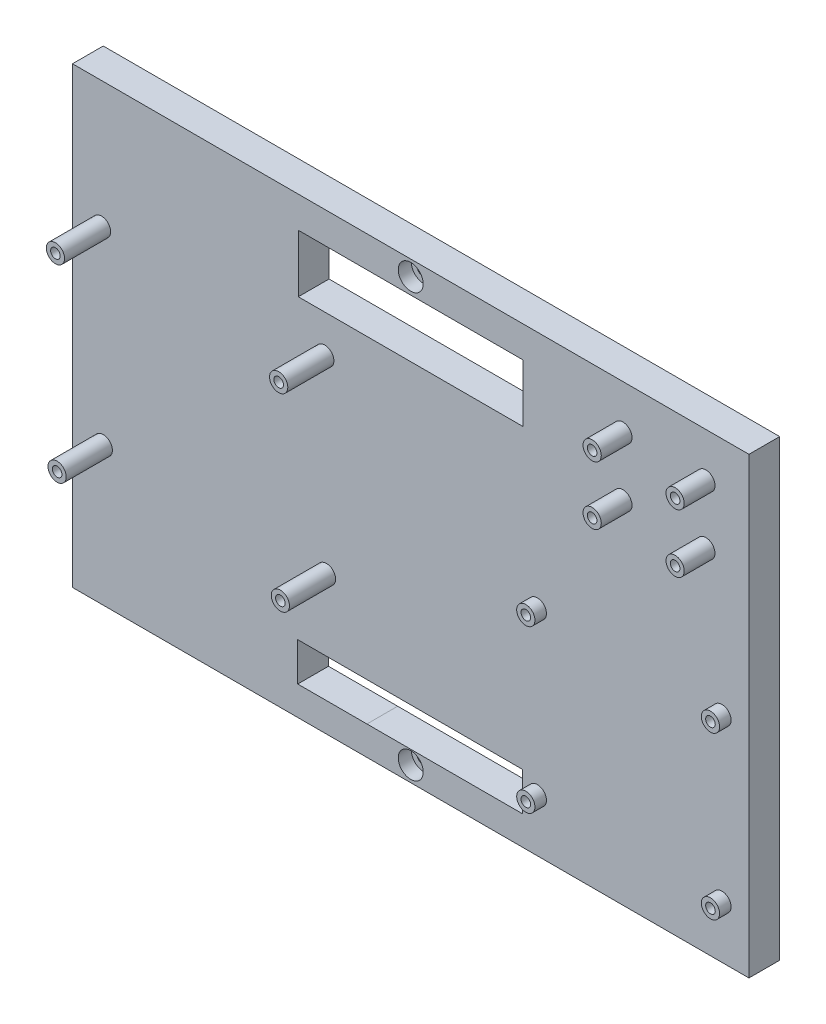
SolidWorks part; units mm, degrees
material "PLA"
ref_plane "Plan de face" through (0, 0, 0) normal (0, 0, 1) x (1, 0, 0)
ref_plane "Plan de dessus" through (0, 0, 0) normal (0, 1, 0) x (1, 0, 0)
ref_plane "Plan de droite" through (0, 0, 0) normal (1, 0, 0) x (0, 0, -1)
sketch "Esquisse1" plane through (0, 0, 0) normal (0, 0, 1) x (1, 0, 0)
  line L0 (-187.1869, -2.6139) -> (-11.1869, -2.6139)
  line L2 (-11.1869, -2.6139) -> (-11.1869, 115.3861)
  line L4 (-187.1869, -2.6139) -> (-187.1869, 115.3861)
  line L10 (-11.1869, 115.3861) -> (-187.1869, 115.3861)
  dimension "D1" = 176
  dimension "D2" = 118
extrude "Boss.-Extru.1" add sketch "Esquisse1" along normal blind 8
sketch "Esquisse5" plane through (0, 0, 8) normal (0, 0, 1) x (1, 0, 0)
  circle A0 centre (-22.394, 103.8949) radius 1.25
  circle A1 centre (-43.984, 88.6549) radius 1.25
  circle A2 centre (-22.394, 88.6549) radius 1.25
  circle A3 centre (-43.984, 103.8949) radius 1.25
  circle A4 centre (-22.394, 103.8949) radius 2.375
  circle A5 centre (-43.984, 88.6549) radius 2.375
  circle A6 centre (-43.984, 103.8949) radius 2.375
  circle A7 centre (-22.394, 88.6549) radius 2.375
  dimension "D1" = 21.59
  dimension "D3" = 15.24
extrude "Boss.-Extru.2" add sketch "Esquisse5" along normal blind 8
sketch "Esquisse6" plane through (0, 0, 8) normal (0, 0, 1) x (1, 0, 0)
  circle A0 centre (-179.1876, 33.4682) radius 1.25
  circle A1 centre (-179.1876, 33.4682) radius 2.375
  circle A2 centre (-121.1021, 33.4675) radius 1.25
  circle A3 centre (-121.1021, 33.4675) radius 2.375
  circle A4 centre (-179.6305, 82.4662) radius 1.25
  circle A5 centre (-179.6305, 82.4662) radius 2.375
  circle A6 centre (-121.545, 82.4655) radius 1.25
  circle A7 centre (-121.545, 82.4655) radius 2.375
  dimension "D1" = 49
  dimension "D2" = 58.0855
  dimension "D3" = 49
  dimension "D4" = 58.0855
extrude "Boss.-Extru.3" add sketch "Esquisse6" along normal blind 12
sketch "Esquisse8" plane through (0, 0, 8) normal (0, 0, 1) x (1, 0, 0)
  circle A0 centre (-18.2019, 11.0773) radius 1.25
  circle A1 centre (-18.2019, 11.0773) radius 2.375
  circle A2 centre (-66.2419, 11.0773) radius 1.25
  circle A3 centre (-66.2419, 11.0773) radius 2.375
  circle A4 centre (-66.2419, 53.1473) radius 1.25
  circle A5 centre (-66.2419, 53.1473) radius 2.375
  circle A6 centre (-18.2019, 53.1473) radius 1.25
  circle A7 centre (-18.2019, 53.1473) radius 2.375
  dimension "D5" = 48.04
  dimension "D6" = 42.07
extrude "Boss.-Extru.4" add sketch "Esquisse8" along normal blind 3
sketch "Esquisse16" plane through (0, 0, 0) normal (0, 0, -1) x (-1, 0, 0)
  line L1 (70.1094, 4.9298) -> (88.1094, 4.9298)
  line L2 (70.1094, 4.9298) -> (70.1094, 14.9298)
  line L3 (70.1094, 14.9298) -> (88.1094, 14.9298)
  line L4 (88.1094, 4.9298) -> (88.1094, 14.9298)
  line L5 (110.581, 4.9296) -> (128.581, 4.9296)
  line L6 (110.581, 4.9296) -> (110.581, 14.9296)
  line L7 (110.581, 14.9296) -> (128.581, 14.9296)
  line L8 (128.581, 4.9296) -> (128.581, 14.9296)
  dimension "D1" = 10
  dimension "D2" = 18
  dimension "D3" = 18
  dimension "D4" = 10
  dimension "D5" = 22.4716
extrude "Enlèv. mat.-Extru.10" cut sketch "Esquisse16" against normal through all
ref_plane "Plan10" through (-99.1869, 0, 0) normal (-1, 0, 0) x (0, 0, 1)
sketch "Esquisse25" plane through (0, 0, 8) normal (0, 0, 1) x (1, 0, 0)
  line L1 (-128.4369, 107.2561) -> (-69.9369, 107.2561)
  line L2 (-128.4369, 107.2561) -> (-128.4369, 92.2561)
  line L3 (-128.4369, 92.2561) -> (-69.9369, 92.2561)
  line L4 (-69.9369, 107.2561) -> (-69.9369, 92.2561)
  line L5 (-11.1869, 115.3861) -> (-187.1869, 115.3861) construction
  line L7 (-11.1869, -2.6139) -> (-11.1869, 115.3861) construction
  dimension "D1" = 58.5
  dimension "D2" = 8.13
  dimension "D3" = 15
  dimension "D4" = 58.75
extrude "Enlèv. mat.-Extru.17" cut sketch "Esquisse25" against normal through all
hole_wizard "Chambrage pour vis à six pans creux M31" positions "Esquisse26" profile "Esquisse28" counterbore size "M3" standard "ISO" end condition through all
sketch "Esquisse26" plane through (0, 0, 8) normal (0, 0, 1) x (1, 0, 0)
  line L6 (-187.1869, 56.3861) -> (-11.1869, 56.3861) construction
  line L7 (-187.1869, 115.3861) -> (-187.1869, -2.6139) construction
  line L8 (-11.1869, -2.6139) -> (-11.1869, 115.3861) construction
  line L10 (-99.1869, 4.4) -> (-99.1869, -4.4) construction
  point P0 (-99.1869, 111.3861)
  point P31 (-99.1869, 1.3861)
  dimension "D1" = 110
sketch "Esquisse28" plane through (-99.1869, 111.3861, 8) normal (1, 0, 0) x (0, -1, 0)
  line L0 (0, 0) -> (0, 8)
  line L1 (0, 8) -> (1.8, 8)
  line L3 (1.8, 8) -> (1.8, 3.4)
  line L4 (1.8, 3.4) -> (3.25, 3.4)
  line L5 (3.25, 3.4) -> (3.25, 0)
  line L7 (3.25, 0) -> (0, 0)
  line L11 (0, -6.35) -> (0, 107.95) construction
  dimension "Diamètre du perçage jusqu'au prochain" = 3.6
  dimension "Profondeur du perçage jusqu'au prochain" = 8
  dimension "Diamètre du chambrage" = 6.5
  dimension "Profondeur du chambrage" = 3.4
sketch "Sketch1" plane through (0, 0, 8) normal (0, 0, 1) x (1, 0, 0)
  line L1 (-110.581, 14.9296) -> (-88.1094, 14.9296)
  line L2 (-110.581, 14.9296) -> (-110.581, 4.9298)
  line L3 (-110.581, 4.9298) -> (-88.1094, 4.9298)
  line L4 (-88.1094, 14.9296) -> (-88.1094, 4.9298)
extrude "Cut-Extrude2" cut sketch "Sketch1" against normal blind 10
